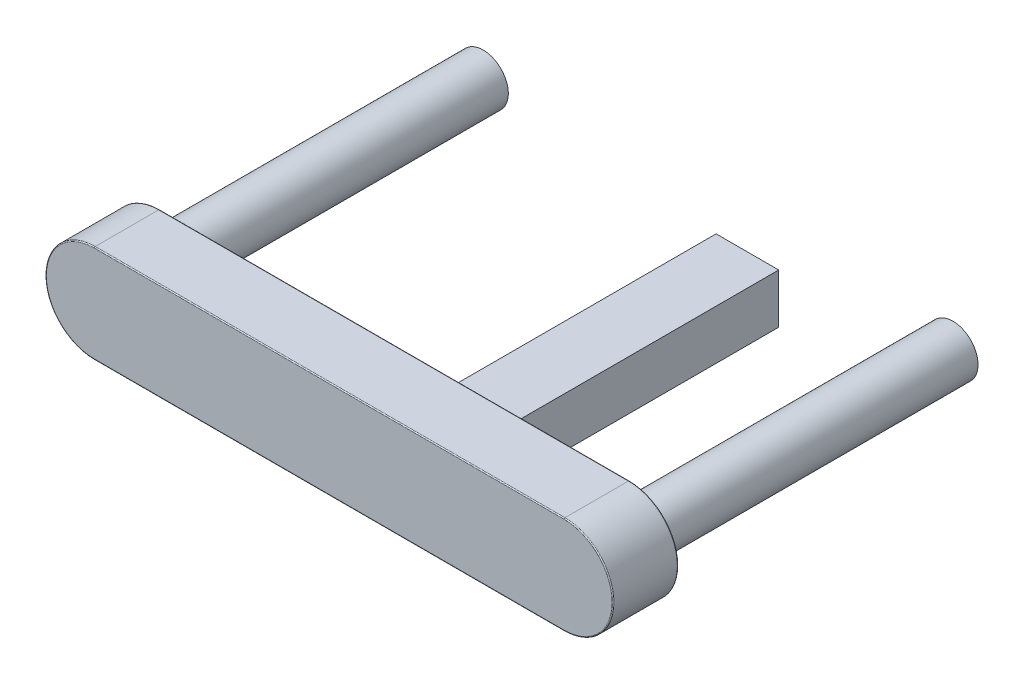
SolidWorks part; units mm, degrees
ref_plane "Front Plane" through (0, 0, 0) normal (0, 0, 1) x (1, 0, 0)
ref_plane "Top Plane" through (0, 0, 0) normal (0, 1, 0) x (1, 0, 0)
ref_plane "Right Plane" through (0, 0, 0) normal (1, 0, 0) x (0, 0, -1)
sketch "Sketch1" plane through (0, 0, 0) normal (0, 0, 1) x (1, 0, 0)
  line L1 (-36, 7.5) -> (36, 7.5) construction
  line L2 (-36, 7.5) -> (-36, -7.5) construction
  line L3 (-36, -7.5) -> (36, -7.5) construction
  line L4 (36, 7.5) -> (36, -7.5) construction
  line L5 (-36, 7.5) -> (36, -7.5) construction
  line L6 (-36, -7.5) -> (36, 7.5) construction
  line L7 (-36, 7.5) -> (36, 7.5)
  line L9 (-36, -7.5) -> (36, -7.5)
  line L11 (-36, 7.5) -> (36, -7.5) construction
  line L12 (-36, -7.5) -> (36, 7.5) construction
  arc A0 (-36, 7.5) -> (-36, -7.5) centre (-36, 0) ccw
  arc A1 (36, -7.5) -> (36, 7.5) centre (36, 0) ccw
  circle A2 centre (-36, 0) radius 4
  circle A3 centre (36, 0) radius 4
  point P0 (0, 0)
  point P12 (0, 0)
  dimension "D3" = 8
  dimension "D1" = 72
  dimension "D2" = 15
  dimension "D4" = 15
extrude "Boss-Extrude1" add sketch "Sketch1" along normal mid plane 10
fillet "Fillet2" radius 0.15 12 edges at (40, 0, -5) (-32, 0, -5) (0, 7.5, -5) (-43.5, 0, -5) (0, -7.5, -5) (43.5, 0, -5) (40, 0, 5) (-43.5, 0, 5) (0, 7.5, 5) (43.5, 0, 5) (0, -7.5, 5) (-32, 0, 5)
sketch "Sketch2" plane through (0, 0, -5) normal (0, 0, -1) x (-1, 0, 0)
  line L0 (-36, 7.5) -> (36, 7.5) construction
  line L1 (-16, 4) -> (-6, 4)
  line L2 (-16, 4) -> (-16, -3.9994)
  line L3 (-16, -3.9994) -> (-6, -3.9994)
  line L4 (-6, 4) -> (-6, -3.9994)
  line L5 (36, -7.5) -> (-36, -7.5) construction
  circle A0 centre (-36, 0) radius 4.15 construction
  dimension "D3" = 20
  dimension "D1" = 3.5
  dimension "D2" = 3.5006
  dimension "D4" = 30
extrude "Cut-Extrude1" cut sketch "Sketch2" against normal blind 3
sketch "Sketch3" plane through (0, 0, -2) normal (0, 0, -1) x (-1, 0, 0)
  line L0 (-16, 4) -> (-6, -3.9994) construction
  line L1 (-16, -3.9994) -> (-6, 4) construction
  circle A0 centre (-11, 0.0003) radius 1.75
  dimension "D1" = 3.5
extrude "Cut-Extrude2" cut sketch "Sketch3" against normal through all
sketch "Sketch4" plane through (0, 0, 5) normal (0, 0, 1) x (1, 0, 0)
  circle A0 centre (36, 0) radius 4.15 construction
  circle A1 centre (-36, 0) radius 4.15 construction
  circle A2 centre (36, 0) radius 4.15
  circle A3 centre (-36, 0) radius 4.15
extrude "Boss-Extrude2" add sketch "Sketch4" against normal up to surface (10 mm away) up to face at (11, 0.0003, -5)
sketch "Sketch5" plane through (0, 0, -5) normal (0, 0, -1) x (-1, 0, 0)
  circle A0 centre (36, 0) radius 4.5
  circle A1 centre (-36, 0) radius 4.5
  dimension "D1" = 9
  dimension "D2" = 9
extrude "Boss-Extrude3" add sketch "Sketch5" along normal blind 0.1
sketch "Sketch6" plane through (0, 0, -5.1) normal (0, 0, -1) x (-1, 0, 0)
  circle A0 centre (-36, 0) radius 3.85
  circle A1 centre (36, 0) radius 3.85
  dimension "D1" = 7.7
  dimension "D2" = 7.7
extrude "Boss-Extrude4" add sketch "Sketch6" along normal blind 49.5
sketch "Sketch9" plane through (0, 0, 5) normal (0, 0, 1) x (1, 0, 0)
  line L0 (15.8, -3.7994) -> (15.8, 3.8)
  line L1 (15.8, 3.8) -> (6.2, 3.8)
  line L6 (6.2, 3.8) -> (6.2, -3.7994)
  line L7 (6.2, -3.7994) -> (15.8, -3.7994)
  line L8 (16, -3.9994) -> (16, 4)
  line L9 (6, -3.9994) -> (16, -3.9994)
  line L10 (6, 4) -> (6, -3.9994)
  line L11 (16, 4) -> (6, 4)
  line L12 (16, -3.9994) -> (16, 4) construction
  line L13 (6, -3.9994) -> (16, -3.9994) construction
  line L14 (6, 4) -> (6, -3.9994) construction
  line L15 (16, 4) -> (6, 4) construction
  dimension "D1" = 0.2
  dimension "D2" = 0
extrude "Boss-Extrude5" add sketch "Sketch9" against normal blind 53.1
sketch "Sketch10" plane through (0, 0, -48.1) normal (0, 0, -1) x (-1, 0, 0)
  line L0 (-15.8, 3.8) -> (-6.2, -3.7994) construction
  line L1 (-6.2, 3.8) -> (-6.2, -3.7994) construction
  line L2 (-6.2, -3.7994) -> (-15.8, -3.7994) construction
  line L3 (-6.2, -3.7994) -> (-6.2, 3.8) construction
  line L4 (-6.2, 3.8) -> (-15.8, -3.7994) construction
  circle A0 centre (-11, 0.0003) radius 1.75
  dimension "D1" = 3.5
extrude "Cut-Extrude3" cut sketch "Sketch10" against normal blind 10 contours A0
